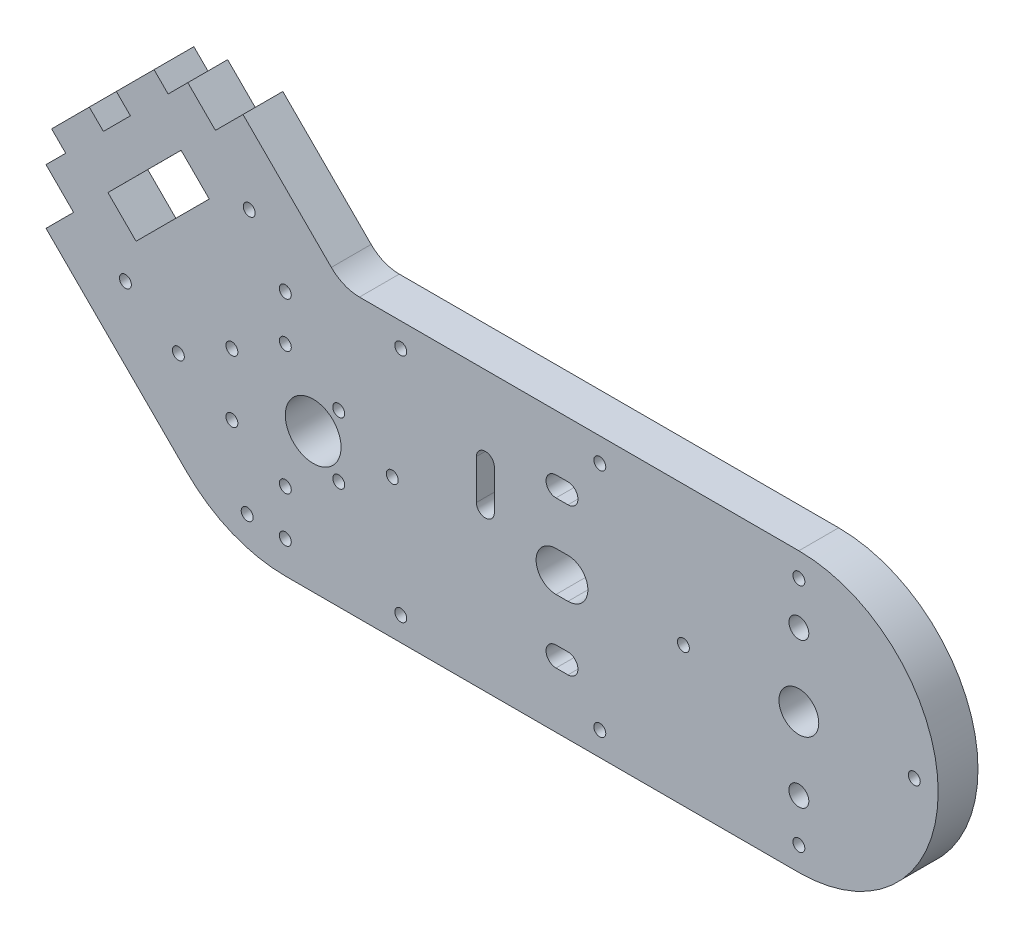
SolidWorks part; units mm, degrees
other "Markup1"
sketch "Sketch2" plane through (35, -35, 0) normal (0.0007, -0.0007, -1) x (0.6809, 0.7324, 0)
ref_plane "Front Plane" through (0, 0, 0) normal (0, 0, 1) x (1, 0, 0)
ref_plane "Top Plane" through (0, 0, 0) normal (0, 1, 0) x (1, 0, 0)
ref_plane "Right Plane" through (0, 0, 0) normal (1, 0, 0) x (0, 0, -1)
sketch "Sketch1" plane through (0, 0, 0) normal (0, 0, 1) x (1, 0, 0)
  line L0 (0, -35) -> (-129, -35)
  line L4 (0, 35) -> (-110.37, 35)
  line L9 (-58, 0) -> (-61, 0) construction
  line L10 (-58, -5) -> (-61, -5)
  line L11 (-58, 5) -> (-61, 5)
  line L13 (-58, 18.5) -> (-61, 18.5) construction
  line L14 (-58, 16) -> (-61, 16)
  line L15 (-58, 21) -> (-61, 21)
  line L17 (-58, -18.5) -> (-61, -18.5) construction
  line L18 (-58, -21) -> (-61, -21)
  line L19 (-58, -16) -> (-61, -16)
  line L20 (-78.75, 5) -> (-78.75, 15) construction
  line L21 (-81, 5) -> (-81, 15)
  line L22 (-76.5, 5) -> (-76.5, 15)
  line L25 (0, 0) -> (-129, 0) construction
  line L27 (-189.1079, 10.5847) -> (-182.1808, 17.5169)
  line L28 (-182.1808, 17.5169) -> (-146.5556, 53.168) construction
  line L29 (-146.5556, 53.168) -> (-139.6285, 60.1002)
  line L30 (-146.5556, 53.168) -> (-153.4878, 60.0952)
  line L31 (-182.1808, 17.5169) -> (-189.113, 24.444)
  line L32 (-189.113, 24.444) -> (-184.1651, 29.3955)
  line L33 (-184.1651, 29.3955) -> (-187.7019, 32.9298)
  line L34 (-153.4878, 60.0952) -> (-158.4357, 55.1436)
  line L35 (-158.4357, 55.1436) -> (-161.9726, 58.6778)
  line L36 (-187.7019, 32.9298) -> (-178.2301, 42.4085)
  line L37 (-184.1651, 29.3955) -> (-158.4357, 55.1436) construction
  line L38 (-178.2301, 42.4085) -> (-174.6933, 38.8742)
  line L39 (-161.9726, 58.6778) -> (-171.4443, 49.1992)
  line L40 (-171.4443, 49.1992) -> (-167.9075, 45.6649)
  line L41 (-174.6933, 38.8742) -> (-167.9075, 45.6649)
  line L43 (-189.1079, 10.5847) -> (-153.7397, -24.7578)
  line L44 (-171.3004, 42.2696) -> (-129, 0) construction
  line L45 (-139.6285, 60.1002) -> (-117.4393, 37.9271)
  line L46 (-173.5573, 26.1467) -> (-155.1792, 44.5382)
  line L47 (-155.1792, 44.5382) -> (-148.1081, 37.4671)
  line L48 (-148.1081, 37.4671) -> (-166.4929, 19.0823)
  line L49 (-166.4929, 19.0823) -> (-173.5573, 26.1467)
  line L54 (-129, 0) -> (-138.5766, -26.3114) construction
  line L55 (-129, 26.8701) -> (-129, -26.8701) construction
  line L56 (-155.8701, 0) -> (-102.1299, 0) construction
  line L57 (-129, 0) -> (-129, 15.5) construction
  line L58 (-129, 0) -> (-149.42, 0) construction
  line L59 (-122, 0) -> (-142.42, 0) construction
  line L60 (-142.42, 0) -> (-142.42, -7.7559) construction
  line L61 (-142.42, 7.7559) -> (-142.42, 0) construction
  line L62 (-122, 0) -> (-122, -7.7559) construction
  line L63 (-122, -7.7559) -> (-115.58, -7.7559) construction
  line L64 (-122, 0) -> (-122, 7.7559) construction
  line L65 (-122, 7.7559) -> (-115.58, 7.7559) construction
  line L66 (0, 0) -> (0, 18.25) construction
  circle A0 centre (0, 0) radius 5
  circle A1 centre (29, 0) radius 1.5
  circle A2 centre (0, -18.25) radius 2.5
  circle A3 centre (0, 18.25) radius 2.5
  arc A4 (0, -35) -> (0, 35) centre (0, 0) ccw
  circle A5 centre (0, 29) radius 1.5
  circle A6 centre (0, -29) radius 1.5
  circle A7 centre (-50, -29) radius 1.5
  circle A8 centre (-50, 29) radius 1.5
  circle A9 centre (-100, -29) radius 1.5
  circle A10 centre (-100, 29) radius 1.5
  arc A11 (-58, -5) -> (-58, 5) centre (-58, 0) ccw
  arc A12 (-61, 5) -> (-61, -5) centre (-61, 0) ccw
  arc A13 (-58, 16) -> (-58, 21) centre (-58, 18.5) ccw
  arc A14 (-61, 21) -> (-61, 16) centre (-61, 18.5) ccw
  arc A15 (-58, -21) -> (-58, -16) centre (-58, -18.5) ccw
  arc A16 (-61, -16) -> (-61, -21) centre (-61, -18.5) ccw
  circle A17 centre (-29, 0) radius 1.5
  arc A18 (-81, 5) -> (-76.5, 5) centre (-78.75, 5) ccw
  arc A19 (-76.5, 15) -> (-81, 15) centre (-78.75, 15) ccw
  arc A22 (-129, -35) -> (-153.7397, -24.7578) centre (-129, 0) cw
  arc A23 (-117.4393, 37.9271) -> (-110.37, 35) centre (-110.37, 45) ccw
  circle A27 centre (-169.167, 9.0363) radius 1.5
  circle A28 centre (-138.0656, 40.1604) radius 1.5
  circle A29 centre (-122, 0) radius 7
  circle A30 centre (-129, 26.8701) radius 1.5
  circle A31 centre (-155.8701, 0) radius 1.5
  circle A32 centre (-129, -26.8701) radius 1.5
  circle A33 centre (-102.1299, 0) radius 1.5
  circle A34 centre (-138.5766, -26.3114) radius 1.5
  circle A35 centre (-129, 15.5) radius 1.5
  circle A37 centre (-129, -15.5) radius 1.5
  circle A38 centre (-142.42, 7.7559) radius 1.5
  circle A39 centre (-142.42, -7.7559) radius 1.5
  circle A40 centre (-115.58, -7.7559) radius 1.5
  circle A41 centre (-115.58, 7.7559) radius 1.5
  point P13 (0, -29)
  point P29 (-59.5, 0)
  point P37 (-59.5, 18.5)
  point P45 (-59.5, -18.5)
  point P54 (-78.75, 10)
  point P74 (-102.28, 58.871)
  point P79 (-122, 0)
  point P86 (-164.3682, 35.3424)
  point P91 (-155.9618, 57.6194)
  dimension "D1" = 10
  dimension "D2" = 5
  dimension "D3" = 5
  dimension "D4" = 70
  dimension "D5" = 3
  dimension "D6" = 3
  dimension "D7" = 3
  dimension "D8" = 3
  dimension "D9" = 3
  dimension "D10" = 3
  dimension "D11" = 3
  dimension "D14" = 50
  dimension "D12" = 35
  dimension "D13" = 35
  dimension "D19" = 5
  dimension "D22" = 36.4
  dimension "D35" = 10
  dimension "D33" = 3
  dimension "D37" = 3
  dimension "D36" = 13
  dimension "D39" = 38
  dimension "D41" = 3
  dimension "D42" = 3
  dimension "D43" = 3
  dimension "D44" = 3
  dimension "D46" = 3
  dimension "D47" = 3
  dimension "D48" = 3
  dimension "D49" = 3
  dimension "D50" = 3
  dimension "D51" = 3
  dimension "D52" = 3
  dimension "D55" = 26.7761
  dimension "D15" = 129
  dimension "D16" = 58
  dimension "D17" = 11
  dimension "D18" = 4.5
  dimension "D20" = 10
  dimension "D21" = 110.37
  dimension "D23" = 50.4
  dimension "D24" = 13.4
  dimension "D25" = 9.8
  dimension "D26" = 9.8
  dimension "D27" = 7
  dimension "D28" = 9.8
  dimension "D29" = 9.8
  dimension "D30" = 5
  dimension "D31" = 5
  dimension "D32" = 13.4
  dimension "D34" = 31.3689
  dimension "D38" = 7
  dimension "D40" = 38
  dimension "D45" = 28
  dimension "D53" = 18.25
  dimension "D54" = 18.25
  dimension "D56" = 7.6513
extrude "Boss-Extrude1" add sketch "Sketch1" along normal blind 10
sketch "Sketch4" plane through (0, 0, 0) normal (0, 0, -1) x (-1, 0, 0)
  line L0 (171.3004, 42.2696) -> (53.1578, -75.8731) construction
  line L1 (167.9075, 45.6649) -> (174.6933, 38.8742) construction
  line L2 (0, 0) -> (64.5154, -64.5154) construction
